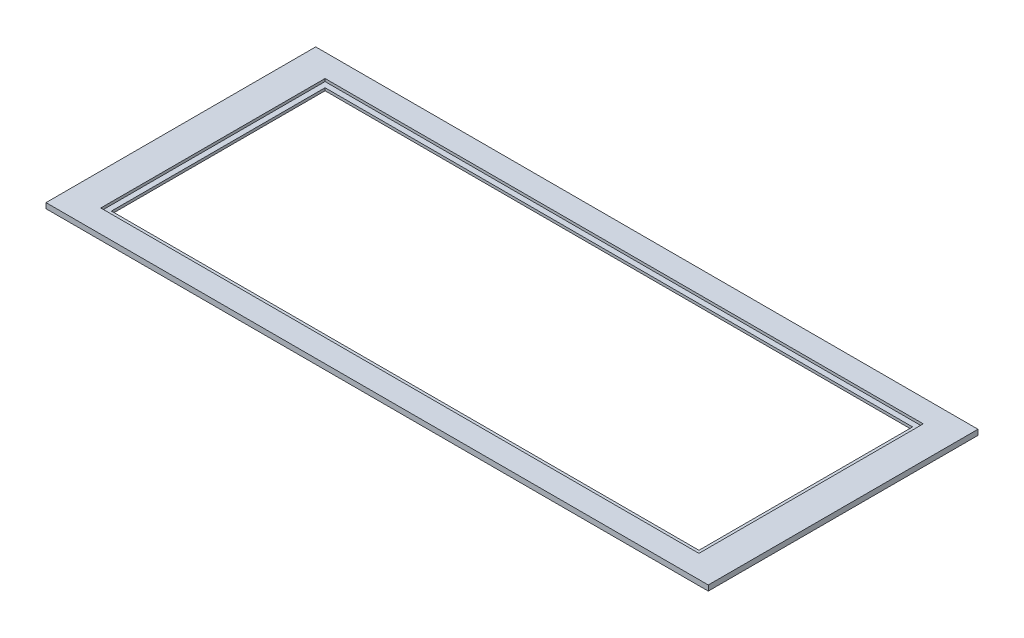
SolidWorks part; units mm, degrees
ref_plane "Front Plane" through (0, 0, 0) normal (0, 0, 1) x (1, 0, 0)
ref_plane "Top Plane" through (0, 0, 0) normal (0, 1, 0) x (1, 0, 0)
ref_plane "Right Plane" through (0, 0, 0) normal (1, 0, 0) x (0, 0, -1)
sketch "Sketch1" plane through (0, 0, 0) normal (0, 1, 0) x (1, 0, 0)
  line L1 (620, 252.5) -> (-620, 252.5)
  line L2 (620, 252.5) -> (620, -252.5)
  line L3 (620, -252.5) -> (-620, -252.5)
  line L4 (-620, 252.5) -> (-620, -252.5)
  line L5 (620, 252.5) -> (-620, -252.5) construction
  line L6 (620, -252.5) -> (-620, 252.5) construction
  point P0 (0, 0)
  dimension "D1" = 505
  dimension "D2" = 1240
extrude "Boss-Extrude1" add sketch "Sketch1" along normal blind 10
sketch "Sketch2" plane through (0, 10, 0) normal (0, 1, 0) x (1, 0, 0)
  line L1 (550, 200) -> (-550, 200)
  line L2 (550, 200) -> (550, -200)
  line L3 (550, -200) -> (-550, -200)
  line L4 (-550, 200) -> (-550, -200)
  line L5 (550, 200) -> (-550, -200) construction
  line L6 (550, -200) -> (-550, 200) construction
  point P0 (0, 0)
  dimension "D1" = 1100
  dimension "D2" = 400
extrude "Cut-Extrude1" cut sketch "Sketch2" against normal through all
sketch "Sketch3" plane through (0, 10, 0) normal (0, 1, 0) x (1, 0, 0)
  line L0 (550, 200) -> (-550, 200) construction
  line L1 (560, 210) -> (-560, 210)
  line L2 (560, 210) -> (560, -210)
  line L3 (560, -210) -> (-560, -210)
  line L4 (-560, 210) -> (-560, -210)
  line L5 (560, 210) -> (-560, -210) construction
  line L6 (560, -210) -> (-560, 210) construction
  line L8 (-550, 200) -> (-550, -200) construction
  point P7 (0, 0)
  point P10 (0, 0)
  point P11 (0, 0)
  dimension "D1" = 10
  dimension "D2" = 10
extrude "Cut-Extrude2" cut sketch "Sketch3" against normal blind 5
equation "\"D2@Sketch1\"=31*4"
